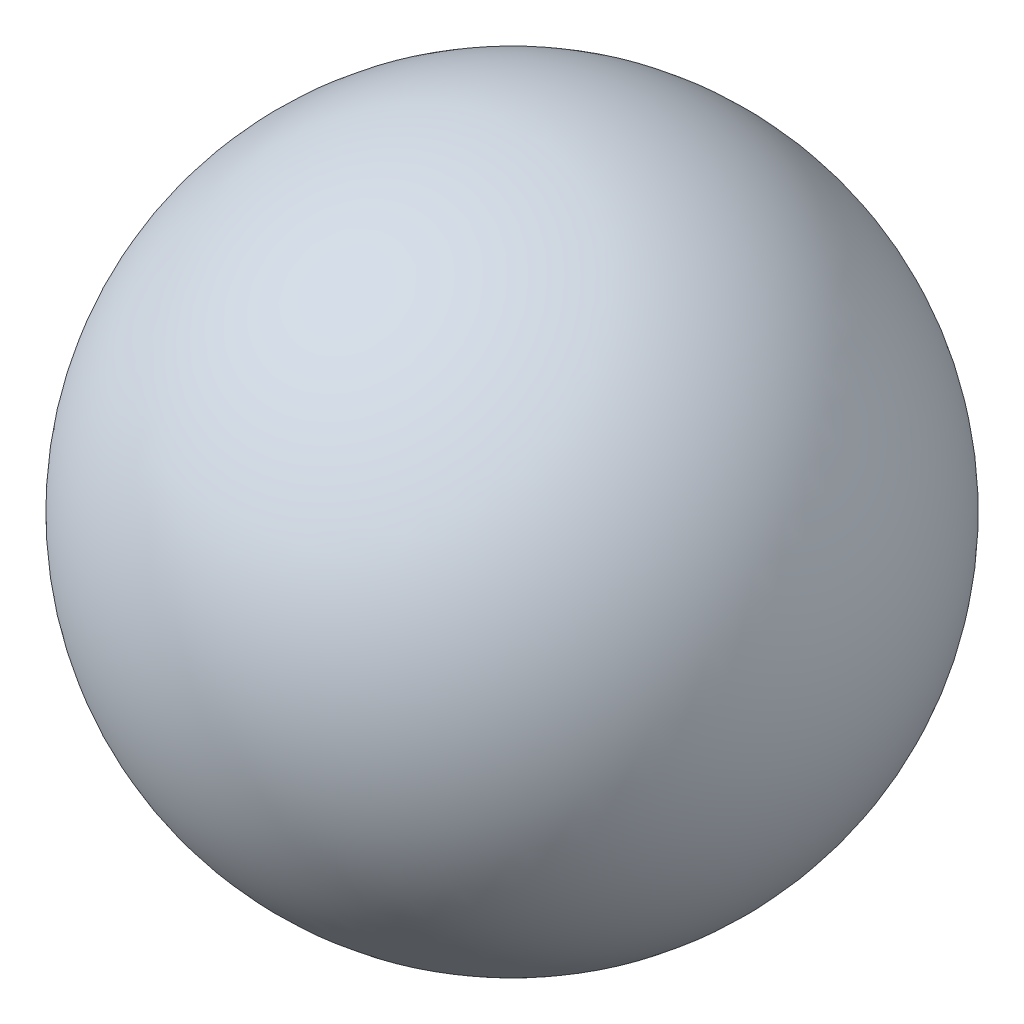
SolidWorks part; units mm, degrees
ref_plane "Plan de face" through (0, 0, 0) normal (0, 0, 1) x (1, 0, 0)
ref_plane "Plan de dessus" through (0, 0, 0) normal (0, 1, 0) x (1, 0, 0)
ref_plane "Plan de droite" through (0, 0, 0) normal (1, 0, 0) x (0, 0, -1)
sketch "Esquisse1" plane through (0, 0, 0) normal (0, 0, 1) x (1, 0, 0)
  line L0 (0, 2.75) -> (0, -2.75) construction
  line L1 (0, 2.75) -> (0, -2.75)
  arc A0 (0, -2.75) -> (0, 2.75) centre (0, 0) ccw
  point P5 (0, 0)
  dimension "D1" = 5.5
revolve "Révolution1" add sketch "Esquisse1" angle 360 about L0
